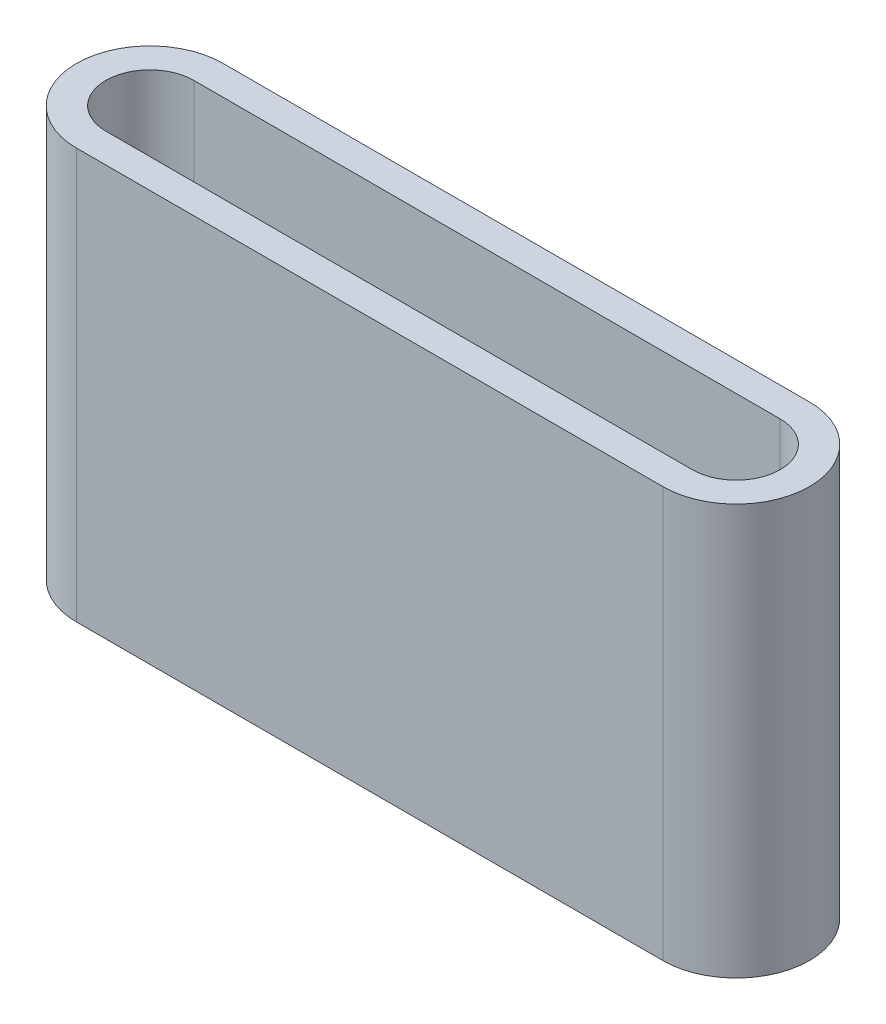
SolidWorks part; units mm, degrees
ref_plane "前视基准面" through (0, 0, 0) normal (0, 0, 1) x (1, 0, 0)
ref_plane "上视基准面" through (0, 0, 0) normal (0, 1, 0) x (1, 0, 0)
ref_plane "右视基准面" through (0, 0, 0) normal (1, 0, 0) x (0, 0, -1)
sketch "草图1" plane through (0, 0, 0) normal (0, 1, 0) x (1, 0, 0)
  line L0 (0, 0) -> (100, 0) construction
  line L1 (0, 12.5) -> (100, 12.5)
  line L2 (0, -12.5) -> (100, -12.5)
  arc A0 (0, 12.5) -> (0, -12.5) centre (0, 0) ccw
  arc A1 (100, -12.5) -> (100, 12.5) centre (100, 0) ccw
  point P3 (50, 0)
  dimension "D1" = 100
  dimension "D2" = 25
extrude "凸台-拉伸1" add sketch "草图1" along normal blind 20 and the other way blind 10
sketch "草图2" plane through (0, 20, 0) normal (0, 1, 0) x (1, 0, 0)
  line L2 (0, -12.5) -> (100, -12.5)
  line L3 (100, 12.5) -> (0, 12.5)
  line L4 (0, -12.5) -> (100, -12.5)
  line L5 (100, 12.5) -> (0, 12.5)
  arc A2 (0, 12.5) -> (0, -12.5) centre (0, 0) ccw
  arc A3 (100, -12.5) -> (100, 12.5) centre (100, 0) ccw
  arc A4 (0, 12.5) -> (0, -12.5) centre (0, 0) ccw
  arc A5 (100, -12.5) -> (100, 12.5) centre (100, 0) ccw
  dimension "D1" = 0
extrude "拉伸-薄壁1" add sketch "草图2" along normal blind 40 thin thin type one direction reverse wall 5
